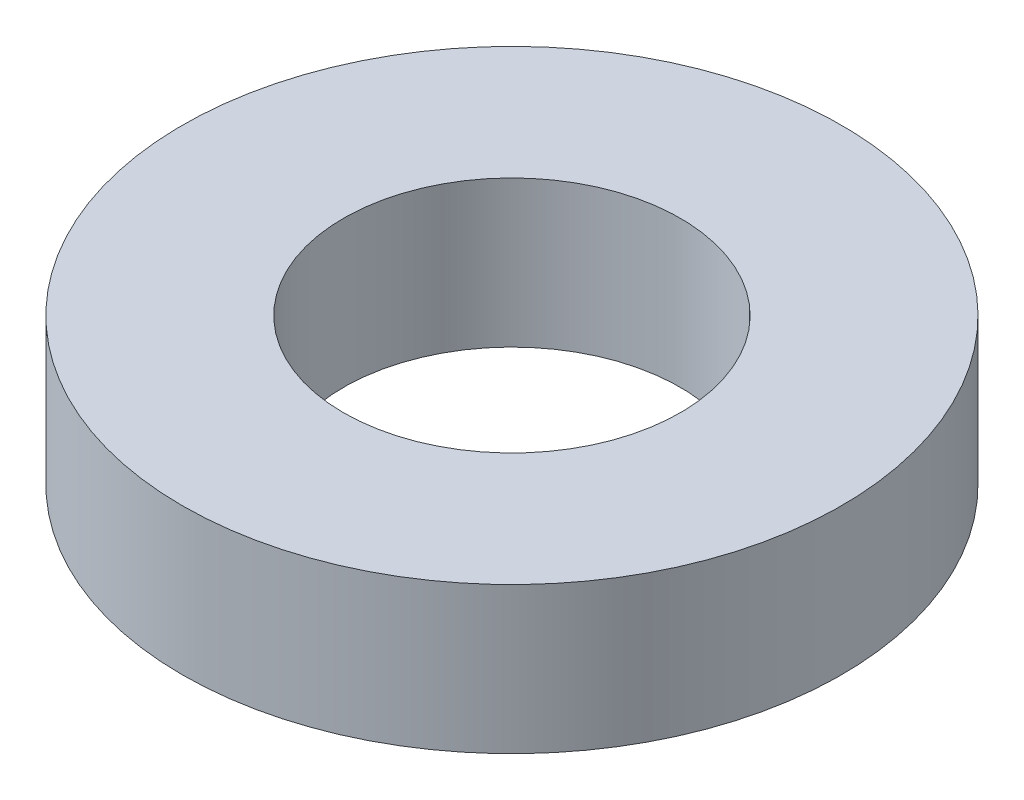
SolidWorks part; units mm, degrees
ref_plane "Front Plane" through (0, 0, 0) normal (0, 0, 1) x (1, 0, 0)
ref_plane "Top Plane" through (0, 0, 0) normal (0, 1, 0) x (1, 0, 0)
ref_plane "Right Plane" through (0, 0, 0) normal (1, 0, 0) x (0, 0, -1)
sketch "Sketch1" plane through (0, 0, 0) normal (0, 1, 0) x (1, 0, 0)
  circle A0 centre (0, 0) radius 2.25
  circle A1 centre (0, 0) radius 1.15
  dimension "D1" = 4.5
  dimension "D2" = 2.3
extrude "Boss-Extrude1" add sketch "Sketch1" along normal blind 1
